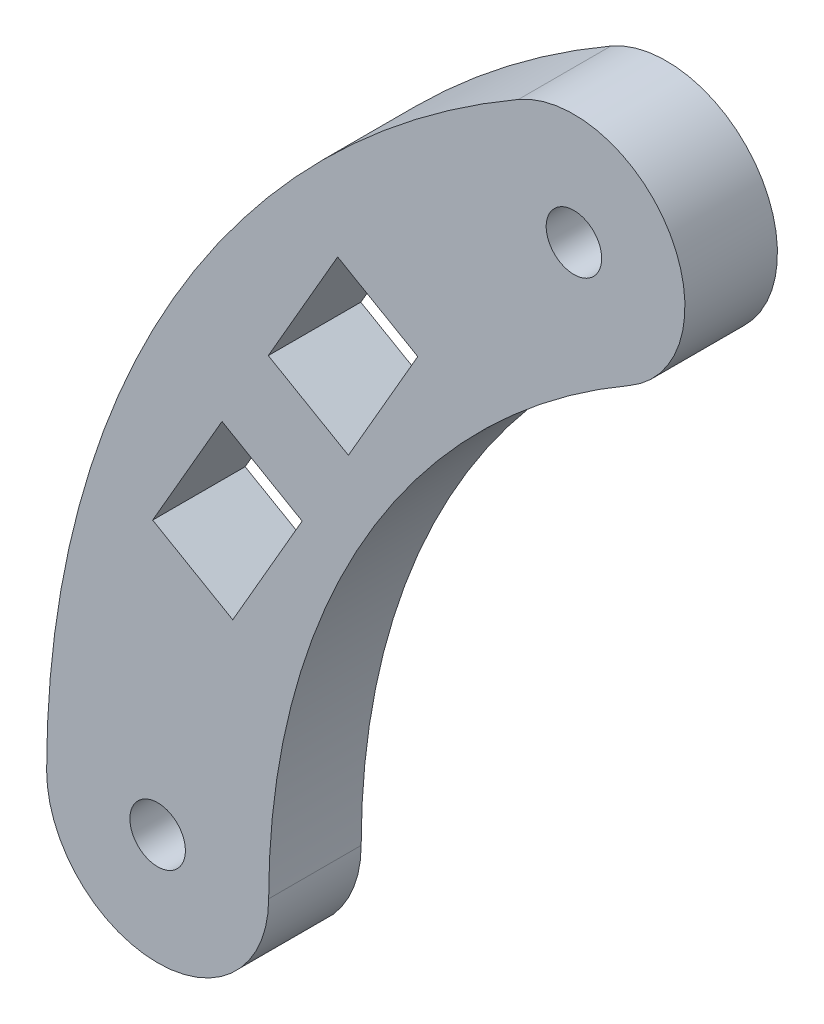
SolidWorks part; units mm, degrees
ref_plane "Plan de face" through (0, 0, 0) normal (0, 0, 1) x (1, 0, 0)
ref_plane "Plan de dessus" through (0, 0, 0) normal (0, 1, 0) x (1, 0, 0)
ref_plane "Plan de droite" through (0, 0, 0) normal (1, 0, 0) x (0, 0, -1)
sketch "Esquisse1" plane through (0, 0, 0) normal (0, 0, 1) x (1, 0, 0)
  line L0 (-22.5, 38.9711) -> (0, 0) construction
  line L1 (0, 0) -> (-45, 0) construction
  line L2 (-46.4244, 7.5905) -> (-29.8397, 36.3162) construction
  line L3 (0, 0) -> (-38.9711, 22.5) construction
  line L4 (-30.9401, 29.4103) -> (-34.6901, 22.9151)
  line L5 (-34.6901, 22.9151) -> (-39.0202, 25.4151)
  line L6 (-39.0202, 25.4151) -> (-35.2702, 31.9103)
  line L7 (-35.2702, 31.9103) -> (-30.9401, 29.4103)
  line L8 (-45.2702, 14.5897) -> (-40.9401, 12.0897)
  line L9 (-41.5202, 21.0849) -> (-45.2702, 14.5897)
  line L10 (-37.1901, 18.5849) -> (-41.5202, 21.0849)
  line L11 (-40.9401, 12.0897) -> (-37.1901, 18.5849)
  arc A0 (-45, 0) -> (-22.5, 38.9711) centre (0, 0) cw construction
  arc A1 (-25.5, 44.1673) -> (-51, 0) centre (0, 0) ccw
  arc A2 (-19.5, 33.775) -> (-39, 0) centre (0, 0) ccw
  arc A3 (-19.5, 33.775) -> (-25.5, 44.1673) centre (-22.5, 38.9711) ccw
  arc A4 (-51, 0) -> (-39, 0) centre (-45, 0) ccw
  circle A5 centre (-22.5, 38.9711) radius 1.5
  circle A6 centre (-45, 0) radius 1.5
  point P4 (-38.9711, 22.5)
  dimension "D1" = 45
  dimension "D2" = 3
  dimension "D3" = 6
  dimension "D4" = 45
  dimension "D5" = 1
  dimension "D6" = 7.5
  dimension "D7" = 5
  dimension "D8" = 2.5
extrude "Boss.-Extru.1" add sketch "Esquisse1" along normal blind 5
